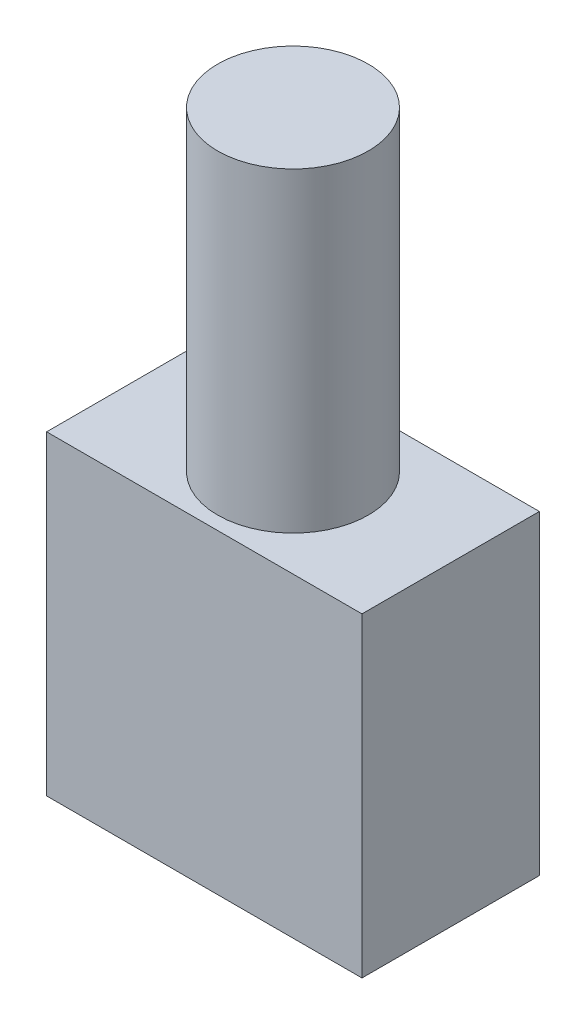
SolidWorks part; units mm, degrees
ref_plane "정면" through (0, 0, 0) normal (0, 0, 1) x (1, 0, 0)
ref_plane "윗면" through (0, 0, 0) normal (0, 1, 0) x (1, 0, 0)
ref_plane "우측면" through (0, 0, 0) normal (1, 0, 0) x (0, 0, -1)
sketch "스케치1" plane through (0, 0, 0) normal (0, 1, 0) x (1, 0, 0)
  line L1 (-40, -22.5) -> (40, -22.5)
  line L2 (-40, -22.5) -> (-40, 22.5)
  line L3 (-40, 22.5) -> (40, 22.5)
  line L4 (40, -22.5) -> (40, 22.5)
  line L5 (-40, -22.5) -> (40, 22.5) construction
  line L6 (-40, 22.5) -> (40, -22.5) construction
  point P0 (0, 0)
  dimension "D1" = 80
  dimension "D2" = 45
extrude "보스-돌출1" add sketch "스케치1" along normal blind 80 contours L2 L3 L4 L1
sketch "스케치3" plane through (0, 80, 0) normal (0, 1, 0) x (1, 0, 0)
  line L0 (-40, -22.5) -> (-40, 22.5) construction
  line L1 (-38, -20.5) -> (38, -20.5)
  line L2 (-38, -20.5) -> (-38, 20.5)
  line L3 (-38, 20.5) -> (38, 20.5)
  line L4 (38, -20.5) -> (38, 20.5)
  line L5 (-38, -20.5) -> (38, 20.5) construction
  line L6 (-38, 20.5) -> (38, -20.5) construction
  line L7 (-40, 22.5) -> (40, 22.5) construction
  point P0 (0, 0)
  dimension "D1" = 2
  dimension "D2" = 2
extrude "컷-돌출1" cut sketch "스케치3" against normal blind 68 draft 3 from offset 1 offset against normal yes
sketch "스케치11" plane through (0, 80, 0) normal (0, 1, 0) x (1, 0, 0)
  circle A0 centre (0, 0) radius 19.1129
extrude "보스-돌출2" add sketch "스케치11" along normal blind 80
